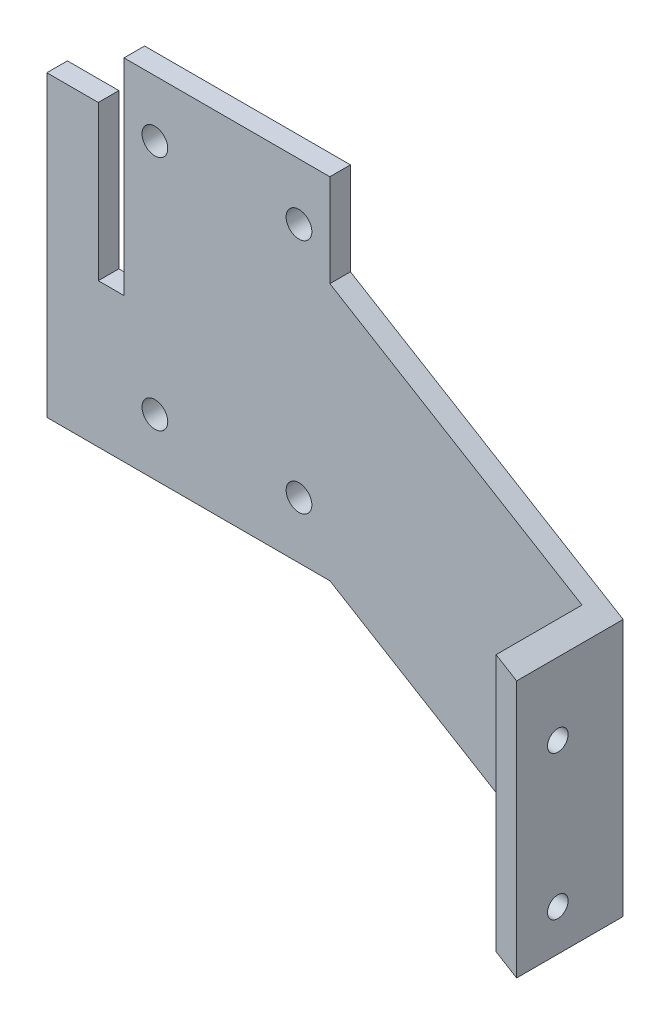
SolidWorks part; units mm, degrees
ref_plane "Спереди" through (0, 0, 0) normal (0, 0, 1) x (1, 0, 0)
ref_plane "Сверху" through (0, 0, 0) normal (0, 1, 0) x (1, 0, 0)
ref_plane "Справа" through (0, 0, 0) normal (1, 0, 0) x (0, 0, -1)
sketch "Эскиз1" plane through (0, 0, 0) normal (0, 0, 1) x (1, 0, 0)
  line L0 (35, 68) -> (35, 0) construction
  line L1 (0, 0) -> (55, 0)
  line L2 (0, 0) -> (0, 68)
  line L3 (0, 68) -> (55, 68)
  line L4 (108, 0) -> (108, 18)
  line L5 (21, 68) -> (21, 0) construction
  line L6 (55, 68) -> (55, 50)
  line L8 (49, 68) -> (49, 0) construction
  line L9 (55, 50) -> (55, 0) construction
  line L10 (108, 0) -> (108, -32)
  line L11 (108, -32) -> (55, 0)
  line L13 (108, 18) -> (55, 50)
  circle A0 centre (21, 57) radius 2.5
  circle A1 centre (49, 57) radius 2.5
  circle A2 centre (21, 11) radius 2.5
  circle A3 centre (49, 11) radius 2.5
  circle A4 centre (93, 0) radius 2.5
  dimension "D8" = 5
  dimension "D9" = 5
  dimension "D10" = 5
  dimension "D11" = 5
  dimension "D18" = 5
  dimension "D1" = 108
  dimension "D2" = 68
  dimension "D3" = 55
  dimension "D4" = 50
  dimension "D5" = 35
  dimension "D6" = 14
  dimension "D7" = 14
  dimension "D12" = 46
  dimension "D13" = 46
  dimension "D14" = 11
  dimension "D15" = 11
  dimension "D16" = 15
  dimension "D17" = 0
  dimension "D19" = 32
extrude "Бобышка-Вытянуть1" add sketch "Эскиз1" along normal blind 4
sketch "Эскиз2" plane through (0, 0, 4) normal (0, 0, 1) x (1, 0, 0)
  line L1 (108, 18) -> (108, -32)
  line L2 (108, -32) -> (104, -29.5849)
  line L3 (55, 0) -> (108, -32) construction
  line L4 (104, -29.5849) -> (104, 20.4151)
  line L5 (108, 18) -> (55, 50) construction
  line L7 (104, 20.4151) -> (108, 18)
  dimension "D1" = 4
extrude "Бобышка-Вытянуть2" add sketch "Эскиз2" along normal blind 16.7
sketch "Эскиз3" plane through (108, 0, 0) normal (1, 0, 0) x (0, 0, -1)
  line L0 (-12.7, 4) -> (-12.7, -24) construction
  line L4 (-20.7, -32) -> (0, -32) construction
  line L6 (-20.7, -32) -> (-20.7, 18) construction
  circle A0 centre (-12.7, 4) radius 2
  circle A1 centre (-12.7, -24) radius 2
  dimension "D2" = 4
  dimension "D3" = 4
  dimension "D1" = 8
  dimension "D4" = 8
  dimension "D5" = 28
extrude "Вырез-Вытянуть1" cut sketch "Эскиз3" against normal blind 10
sketch "Эскиз4" plane through (0, 0, 4) normal (0, 0, 1) x (1, 0, 0)
  line L1 (0, 68) -> (15, 68)
  line L2 (0, 68) -> (0, 58)
  line L3 (0, 58) -> (10, 58)
  line L4 (15, 68) -> (15, 58)
  line L6 (15, 58) -> (15, 28)
  line L7 (15, 28) -> (10, 28)
  line L8 (10, 58) -> (10, 28)
  dimension "D1" = 15
  dimension "D2" = 10
  dimension "D3" = 40
  dimension "D4" = 5
extrude "Вырез-Вытянуть2" cut sketch "Эскиз4" against normal blind 10
